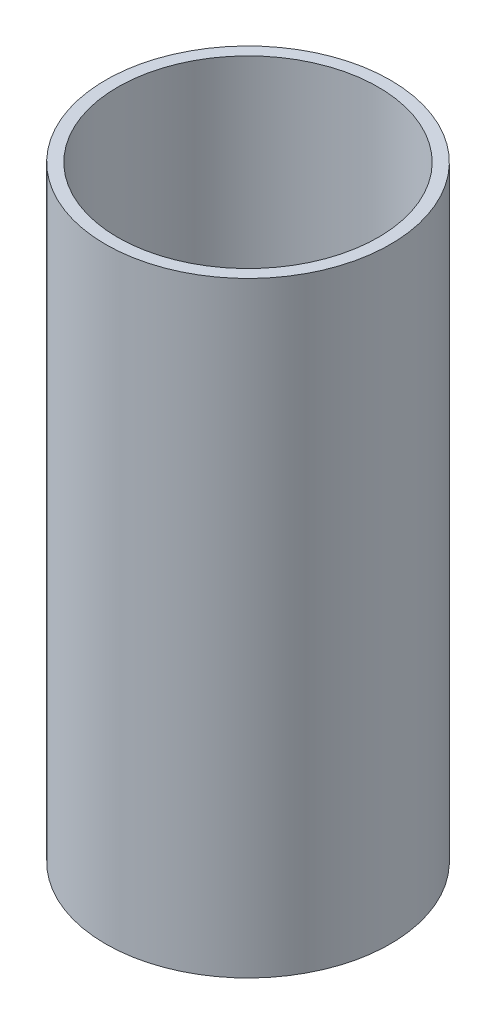
SolidWorks part; units mm, degrees
ref_plane "Front Plane" through (0, 0, 0) normal (0, 0, 1) x (1, 0, 0)
ref_plane "Top Plane" through (0, 0, 0) normal (0, 1, 0) x (1, 0, 0)
ref_plane "Right Plane" through (0, 0, 0) normal (1, 0, 0) x (0, 0, -1)
sketch "Sketch1" plane through (0, 0, 0) normal (0, 1, 0) x (1, 0, 0)
  circle A0 centre (0, 0) radius 2.15
  circle A1 centre (0, 0) radius 2.35
  dimension "D1" = 4.3
  dimension "D2" = 4.7
extrude "Boss-Extrude1" add sketch "Sketch1" along normal mid plane 10
